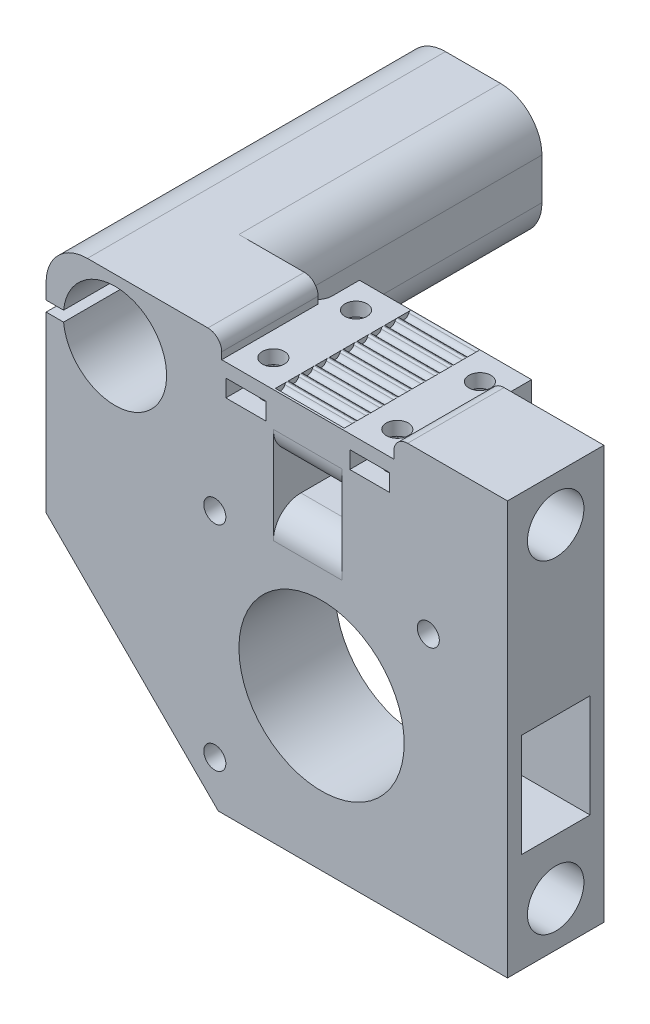
SolidWorks part; units mm, degrees
material "ABS"
ref_plane "Plano frontal" through (0, 0, 0) normal (0, 0, 1) x (1, 0, 0)
ref_plane "Plano superior" through (0, 0, 0) normal (0, 1, 0) x (1, 0, 0)
ref_plane "Plano direito" through (0, 0, 0) normal (1, 0, 0) x (0, 0, -1)
sketch "Esboço1" plane through (0, 0, 0) normal (0, 0, 1) x (1, 0, 0)
  line L0 (0, 30) -> (0, -30) construction
  line L1 (-10, 30) -> (10, 30)
  line L2 (-10, 30) -> (-10, -30)
  line L3 (-10, -30) -> (10, -30)
  line L4 (10, 30) -> (10, -30)
  line L5 (-10, 30) -> (10, -30) construction
  line L6 (-10, -30) -> (10, 30) construction
  line L7 (-10, 21) -> (10, 21) construction
  line L8 (-7.4624, 20.25) -> (-10, 20.25)
  line L9 (-7.4624, 20.25) -> (-7.4624, 21.75)
  line L10 (-10, 20.25) -> (-10, 21.75)
  line L11 (-7.4624, 21.75) -> (-10, 21.75)
  line L12 (-7.4624, 20.25) -> (-10, 21.75) construction
  line L13 (-10, 20.25) -> (-7.4624, 21.75) construction
  circle A0 centre (0, 21) radius 7.5
  point P0 (0, 0)
  point P13 (-8.7312, 21)
  dimension "D3" = 15
  dimension "D1" = 60
  dimension "D2" = 20
  dimension "D4" = 9
  dimension "D5" = 1.5
extrude "Ressalto-extrusão2" add sketch "Esboço1" along normal mid plane 52
sketch "Esboço4" plane through (10, 0, 0) normal (1, 0, 0) x (0, 0, -1)
  line L1 (26, -30) -> (-12, -30)
  line L2 (26, -30) -> (26, 12)
  line L3 (26, 12) -> (-12, 12)
  line L4 (-12, -30) -> (-12, 12)
  line L5 (-26, 30) -> (-26, -30) construction
  line L6 (-26, 30) -> (26, 30) construction
  dimension "D1" = 18
  dimension "D2" = 14
extrude "Corte-extrusão1" cut sketch "Esboço4" against normal through all
sketch "Esboço5" plane through (10, 0, 0) normal (1, 0, 0) x (0, 0, -1)
  line L0 (-26, 30) -> (26, 30) construction
  line L1 (-26, -30) -> (-12, -30)
  line L2 (-26, -30) -> (-26, 30)
  line L3 (-26, 30) -> (-12, 30)
  line L4 (-12, -30) -> (-12, 30)
  dimension "D1" = 14
extrude "Ressalto-extrusão3" add sketch "Esboço5" along normal blind 47
sketch "Esboço6" plane through (57, 0, 0) normal (1, 0, 0) x (0, 0, -1)
  line L0 (-19, 30) -> (-19, -30) construction
  line L1 (-12, 30) -> (-26, 30) construction
  line L2 (-26, -30) -> (-12, -30) construction
  line L3 (-26, 0) -> (-12, 0) construction
  line L4 (-26, 30) -> (-26, -30) construction
  line L5 (-12, -30) -> (-12, 30) construction
  circle A0 centre (-19, 23.5) radius 4.1
  circle A1 centre (-19, -23.5) radius 4.1
  dimension "D1" = 8.2
  dimension "D2" = 23.5
sketch "Esboço8" plane through (0, 0, 26) normal (0, 0, 1) x (1, 0, 0)
  line L0 (-10, -8) -> (57, -8) construction
  line L1 (-10, 20.25) -> (-10, -30) construction
  line L3 (57, 30) -> (57, -30) construction
  line L4 (-10, -30) -> (57, -30) construction
  circle A0 centre (30, -8) radius 12
  circle A1 centre (45.5, 7.5) radius 1.6
  circle A3 centre (30, -8) radius 12
  circle A4 centre (14.5, -23.5) radius 1.6
  circle A5 centre (30, -8) radius 12
  circle A6 centre (14.5, 7.5) radius 1.6
  circle A7 centre (30, -8) radius 12
  circle A8 centre (45.5, -23.5) radius 1.6 [skipped]
  point P22 (30, -8)
  dimension "D1" = 24
  dimension "D6" = 3.2
  dimension "D2" = 15.5
  dimension "D3" = 15.5
  dimension "D4" = 22
  dimension "D7" = 40
  dimension "D5" = 4
extrude "Corte-extrusão3" cut sketch "Esboço8" against normal through all
extrude "Corte-extrusão4" cut sketch "Esboço6" against normal blind 15
sketch "Esboço10" plane through (57, 0, 0) normal (1, 0, 0) x (0, 0, -1)
  line L0 (-19, 30) -> (-19, -30) construction
  line L1 (-12, 30) -> (-26, 30) construction
  line L2 (-26, -30) -> (-12, -30) construction
  line L3 (-26, 30) -> (-26, -30) construction
  line L4 (-24, -0.5) -> (-14, -0.5)
  line L5 (-24, -0.5) -> (-24, -15.5)
  line L6 (-24, -15.5) -> (-14, -15.5)
  line L7 (-14, -0.5) -> (-14, -15.5)
  line L8 (-24, -0.5) -> (-14, -15.5) construction
  line L9 (-24, -15.5) -> (-14, -0.5) construction
  line L10 (-12, -30) -> (-12, 30) construction
  circle A0 centre (-19, 23.5) radius 4.1 construction
  circle A1 centre (-19, -23.5) radius 4.1 construction
  dimension "D1" = 2
  dimension "D2" = 24
  dimension "D3" = 8
  dimension "D4" = 2
extrude "Corte-extrusão5" cut sketch "Esboço10" against normal up to next
sketch "Esboço12" plane through (0, 0, 12) normal (0, 0, -1) x (-1, 0, 0)
  line L0 (-57, 30) -> (-10, 30) construction
  line L1 (-40.5, 30) -> (-15.5, 30)
  line L2 (-40.5, 30) -> (-40.5, 18)
  line L3 (-40.5, 18) -> (-15.5, 18)
  line L4 (-15.5, 30) -> (-15.5, 18)
  line L5 (10, 30) -> (10, 21.75) construction
  dimension "D1" = 25
  dimension "D2" = 12
  dimension "D3" = 25.5
extrude "Ressalto-extrusão4" add sketch "Esboço12" along normal blind 6
sketch "Esboço11" plane through (0, 0, 12) normal (0, 0, -1) x (-1, 0, 0)
  line L1 (-40.5, 30) -> (-15.5, 30)
  line L2 (-40.5, 30) -> (-40.5, 27)
  line L3 (-40.5, 27) -> (-15.5, 27)
  line L4 (-15.5, 30) -> (-15.5, 27)
  line L5 (-40.5, 30) -> (-40.5, 18) construction
  line L6 (-57, 30) -> (-40.5, 30) construction
  dimension "D1" = 25
  dimension "D2" = 3
extrude "Corte-extrusão6" cut sketch "Esboço11" against normal through all and the other way through all
sketch "Esboço13" plane through (0, 0, 12) normal (0, 0, -1) x (-1, 0, 0)
  line L0 (-40.5, 18) -> (-15.5, 18) construction
  line L1 (-23, 18) -> (-33, 18)
  line L2 (-23, 18) -> (-23, 12)
  line L3 (-23, 12) -> (-33, 12)
  line L4 (-33, 18) -> (-33, 12)
  point P5 (-28, 18)
  point P8 (-28, 18)
  dimension "D1" = 10
  dimension "D2" = 6
extrude "Corte-extrusão7" cut sketch "Esboço13" against normal through all
fillet "Filete5" radius 4 4 edges at (28, 12, 26) (28, 18, 6) (28, 18, 26) (28, 12, 12)
fillet "Filete6" radius 6 4 edges at (10, 12, -7) (-10, 12, -7) (-10, 30, 0) (10, 30, -7)
ref_plane "Plano1" through (0, 0, 0) normal (0, 0, 1) x (1, 0, 0)
fillet "Filete8" radius 2 2 edges at (40.5, 22.5, 12) (15.5, 22.5, 12)
fillet "Filete9" radius 2 2 edges at (15.5, 30, 19) (40.5, 30, 19)
sketch "Esboço14" plane through (0, 27, 0) normal (0, 1, 0) x (1, 0, 0)
  line L0 (28, -26) -> (28, -6) construction
  line L1 (40.5, -26) -> (15.5, -26) construction
  line L2 (40.5, -6) -> (15.5, -6) construction
  line L3 (15.5, -16) -> (40.5, -16) construction
  line L6 (40.5, -26) -> (15.5, -26) construction
  line L8 (15.5, -26) -> (15.5, -12) construction
  line L9 (40.5, -26) -> (40.5, -12) construction
  circle A0 centre (19, -22) radius 1.6
  circle A1 centre (37, -22) radius 1.6
  circle A2 centre (37, -10) radius 1.6
  circle A3 centre (19, -10) radius 1.6
  dimension "D1" = 3.2
  dimension "D2" = 6
  dimension "D3" = 9
  dimension "D4" = 10
extrude "Corte-extrusão8" cut sketch "Esboço14" against normal blind 8
sketch "Esboço15" plane through (0, 0, 26) normal (0, 0, 1) x (1, 0, 0)
  line L0 (40.5, 27) -> (15.5, 27) construction
  line L1 (16.1, 25) -> (21.9, 25)
  line L2 (16.1, 25) -> (16.1, 22.5)
  line L3 (16.1, 22.5) -> (21.9, 22.5)
  line L4 (21.9, 25) -> (21.9, 22.5)
  line L5 (28, 27) -> (28, -30) construction
  line L6 (-10, -30) -> (57, -30) construction
  line L7 (39.9, 25) -> (39.9, 22.5)
  line L8 (39.9, 22.5) -> (34.1, 22.5)
  line L9 (34.1, 25) -> (34.1, 22.5)
  line L10 (39.9, 25) -> (34.1, 25)
  point P4 (19, 25)
  dimension "D1" = 2.5
  dimension "D2" = 5.8
  dimension "D3" = 3.5
  dimension "D4" = 2
extrude "Corte-extrusão9" cut sketch "Esboço15" against normal blind 7
ref_plane "Plano2" through (0, 0, 16) normal (0, 0, 1) x (1, 0, 0)
mirror "Espelhar1" about plane through (0, 0, 16) normal (0, 0, 1) of "Corte-extrusão9"
ref_plane "Plano3" through (28, 0, 0) normal (1, 0, 0) x (0, 0, -1)
sketch "Esboço16" plane through (28, 0, 0) normal (1, 0, 0) x (0, 0, -1)
  line L0 (-10, 27) -> (-6, 27) construction
  line L1 (-7.7, 27) -> (-6.3, 27)
  arc A0 (-6.3, 27) -> (-7.7, 27) centre (-7, 27) cw
  dimension "D1" = 0.7
  dimension "D2" = 1
extrude "Corte-extrusão10" cut sketch "Esboço16" against normal blind 5 and the other way blind 5
pattern_linear "Padrão linear1" count 10 spacing 2 along (0, 0, 1) of "Corte-extrusão10"
fillet "Filete10" radius 0.3 19 edges at (28, 27, 24.3) (28, 27, 23.7) (28, 27, 22.3) (28, 27, 21.7) (28, 27, 20.3) (28, 27, 19.7) (28, 27, 18.3) (28, 27, 17.7) (28, 27, 16.3) (28, 27, 15.7) (28, 27, 14.3) (28, 27, 13.7) (28, 27, 12.3) (28, 27, 11.7) (28, 27, 10.3) (28, 27, 9.7) (28, 27, 8.3) (28, 27, 7.7) (28, 27, 6.3)
chamfer "Chanfro1" distance 25 angle 45 1 edges at (-10, -30, 19)
